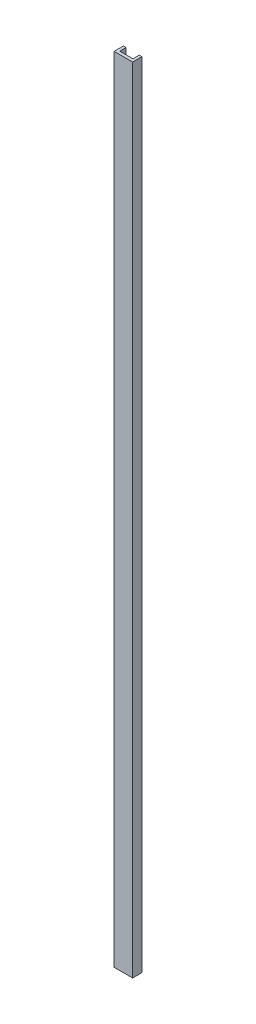
SolidWorks part; units mm, degrees
ref_plane "前视基准面" through (0, 0, 0) normal (0, 0, 1) x (1, 0, 0)
ref_plane "上视基准面" through (0, 0, 0) normal (0, 1, 0) x (1, 0, 0)
ref_plane "右视基准面" through (0, 0, 0) normal (1, 0, 0) x (0, 0, -1)
other "Configuration Table"
sketch "草图1" plane through (0, 0, 0) normal (0, 1, 0) x (1, 0, 0)
  line L0 (-10, 7) -> (-10, -2.5)
  line L1 (14, -7) -> (-14, -7)
  line L2 (14, -7) -> (14, 7)
  line L3 (14, 7) -> (10, 7)
  line L4 (-14, -7) -> (-14, 7)
  line L5 (14, -7) -> (-14, 7) construction
  line L6 (14, 7) -> (-14, -7) construction
  line L7 (-10, -2.5) -> (10, -2.5)
  line L8 (10, -2.5) -> (10, 7)
  line L9 (-10, 7) -> (-14, 7)
  point P0 (0, 0)
  dimension "D1" = 28
  dimension "D2" = 14
  dimension "D3" = 9.5
  dimension "D4" = 4
  dimension "D5" = 4
extrude "凸台-拉伸1" add sketch "草图1" along normal blind 1200
